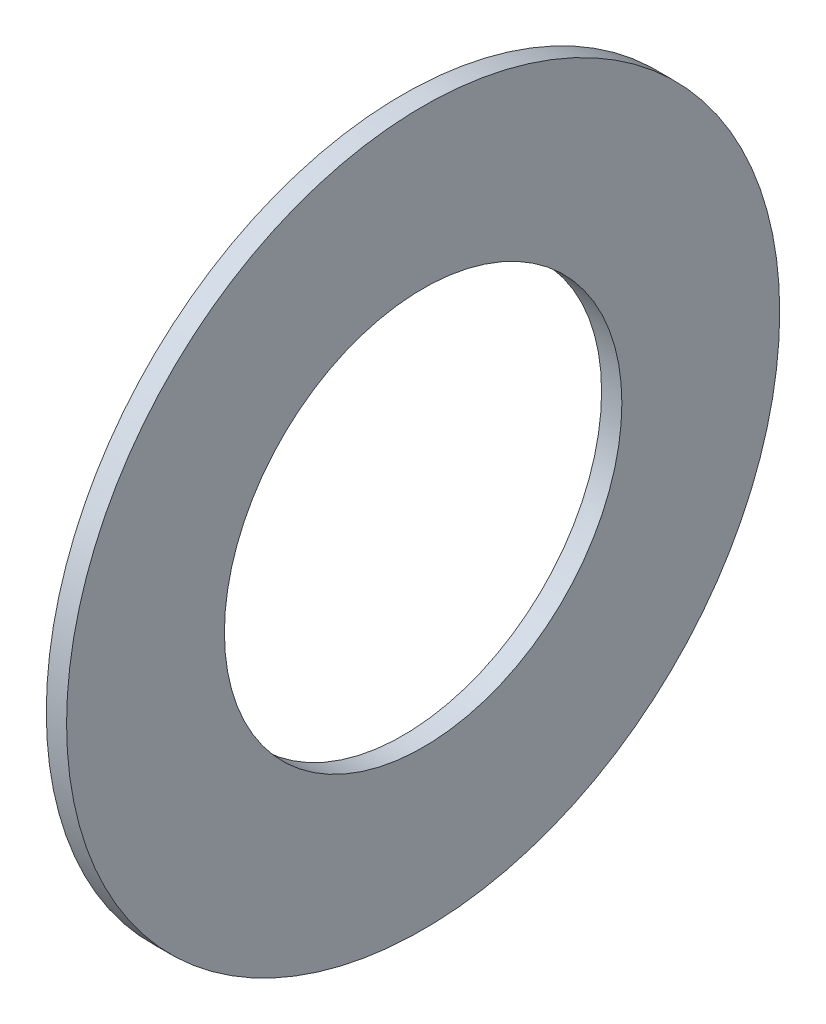
SolidWorks part; units mm, degrees
material "Alloy Steel"
ref_plane "Front Plane" through (0, 0, 0) normal (0, 0, 1) x (1, 0, 0)
ref_plane "Top Plane" through (0, 0, 0) normal (0, 1, 0) x (1, 0, 0)
ref_plane "Right Plane" through (0, 0, 0) normal (1, 0, 0) x (0, 0, -1)
sketch "Sketch1" plane through (0, 0, 0) normal (1, 0, 0) x (0, 0, -1)
  circle A0 centre (0, 0) radius 14.2875
  circle A1 centre (0, 0) radius 7.9629
  dimension "OD" = 28.575
  dimension "Shaft Dia" = 15.9258
extrude "Extrude1" add sketch "Sketch1" along normal blind 0.8128
